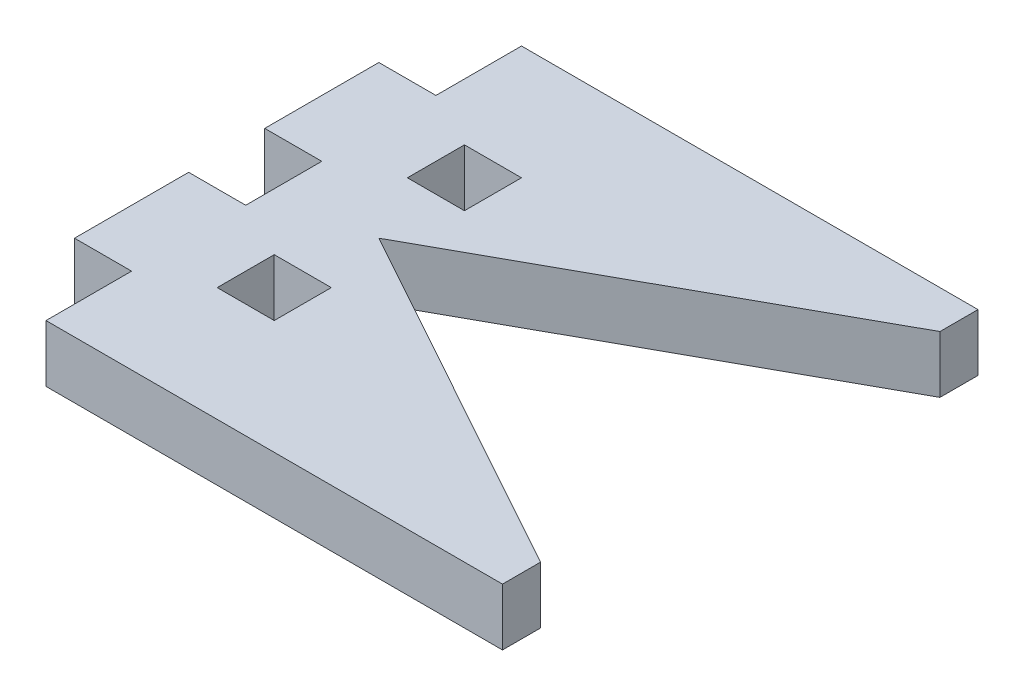
SolidWorks part; units mm, degrees
ref_plane "Front Plane" through (0, 0, 0) normal (0, 0, 1) x (1, 0, 0)
ref_plane "Top Plane" through (0, 0, 0) normal (0, 1, 0) x (1, 0, 0)
ref_plane "Right Plane" through (0, 0, 0) normal (1, 0, 0) x (0, 0, -1)
sketch "Sketch1" plane through (0, 0, 0) normal (0, 1, 0) x (1, 0, 0)
  line L0 (-5.5, 0) -> (13.5, 10.5)
  line L1 (-10.5, 12.5) -> (13.5, 12.5)
  line L2 (-13.5, 8) -> (-13.5, 2)
  line L3 (-10.5, -12.5) -> (13.5, -12.5)
  line L4 (13.5, 12.5) -> (13.5, 10.5)
  line L5 (-10.5, -8) -> (-10.5, -12.5)
  line L6 (-13.5, -2) -> (-13.5, -8)
  line L7 (-5.5, 0) -> (13.5, -10.5)
  line L8 (13.5, -10.5) -> (13.5, -12.5)
  line L10 (-13.5, 8) -> (-10.5, 8)
  line L11 (-13.5, 2) -> (-10.5, 2)
  line L12 (-10.5, 2) -> (-10.5, -2)
  line L13 (-13.5, -2) -> (-10.5, -2)
  line L16 (-13.5, -8) -> (-10.5, -8)
  line L17 (-10.5, 8) -> (-10.5, 12.5)
  point P0 (0, 0)
  dimension "D1" = 25
  dimension "D3" = 19
  dimension "D4" = 2
  dimension "D5" = 2
  dimension "D7" = 6
  dimension "D8" = 6
  dimension "D10" = 3
  dimension "D11" = 3
extrude "Boss-Extrude1" add sketch "Sketch1" along normal blind 3
sketch "Sketch2" plane through (0, 3, 0) normal (0, 1, 0) x (1, 0, 0)
  line L0 (-7.5, 13.6384) -> (-7.5, -14.5741) construction
  line L1 (-10.5, 12.5) -> (-10.5, 8) construction
  line L2 (-7.5, 6.5) -> (-7.5, 3.5)
  line L3 (-7.5, 6.5) -> (-4.5, 6.5)
  line L4 (-7.5, 3.5) -> (-4.5, 3.5)
  line L5 (-4.5, 6.5) -> (-4.5, 3.5)
  line L6 (-7.5, -3.5) -> (-7.5, -6.5)
  line L7 (-7.5, -3.5) -> (-4.5, -3.5)
  line L8 (-7.5, -6.5) -> (-4.5, -6.5)
  line L9 (-4.5, -3.5) -> (-4.5, -6.5)
  line L10 (-10.5, -12.5) -> (13.5, -12.5) construction
  line L11 (13.5, 12.5) -> (-10.5, 12.5) construction
  point P4 (-4.5, -5)
  point P15 (-4.5, 5)
  dimension "D1" = 3
  dimension "D2" = 3
  dimension "D3" = 3
  dimension "D4" = 3
  dimension "D5" = 3
  dimension "D6" = 7.5
  dimension "D7" = 7.5
extrude "Cut-Extrude1" cut sketch "Sketch2" against normal blind 3
